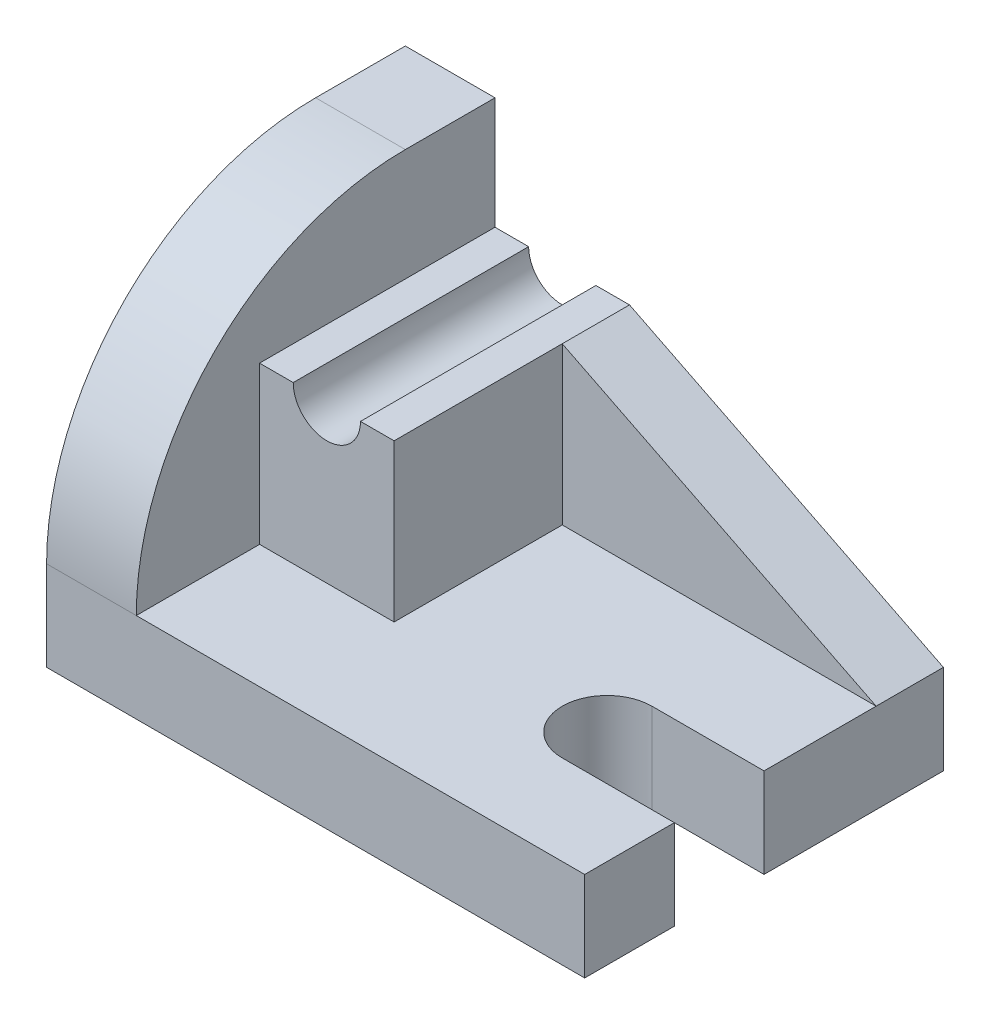
SolidWorks part; units mm, degrees
ref_plane "Front Plane" through (0, 0, 0) normal (0, 0, 1) x (1, 0, 0)
ref_plane "Top Plane" through (0, 0, 0) normal (0, 1, 0) x (1, 0, 0)
ref_plane "Right Plane" through (0, 0, 0) normal (1, 0, 0) x (0, 0, -1)
sketch "Sketch2" plane through (0, 0, 0) normal (0, 1, 0) x (1, 0, 0)
  line L1 (-48, -32) -> (48, -32)
  line L2 (-48, -32) -> (-48, 32)
  line L3 (-48, 32) -> (48, 32)
  line L4 (48, -32) -> (48, 32)
  line L5 (-48, -32) -> (48, 32) construction
  line L6 (-48, 32) -> (48, -32) construction
  point P0 (0, 0)
  dimension "D1" = 96
  dimension "D2" = 64
extrude "Boss-Extrude1" add sketch "Sketch2" along normal blind 16
sketch "Sketch5" plane through (0, 16, 0) normal (0, 1, 0) x (1, 0, 0)
  line L0 (48, -8) -> (28, -8) construction
  line L1 (48, -32) -> (48, 32) construction
  line L2 (48, -16) -> (28, -16)
  line L3 (48, 0) -> (28, 0)
  line L4 (-48, -32) -> (48, -32) construction
  arc A0 (48, -16) -> (48, 0) centre (48, -8) ccw
  arc A1 (28, 0) -> (28, -16) centre (28, -8) ccw
  point P4 (38, -8)
  dimension "D1" = 16
  dimension "D2" = 20
  dimension "D3" = 16
extrude "Cut-Extrude1" cut sketch "Sketch5" against normal blind 16
sketch "Sketch10" plane through (-48, 0, 0) normal (-1, 0, 0) x (0, 0, 1)
  line L1 (32, 0) -> (-32, 0)
  line L2 (32, 0) -> (32, 16)
  line L3 (-16, 64) -> (-32, 64)
  line L4 (-32, 0) -> (-32, 64)
  arc A0 (32, 16) -> (-16, 64) centre (-16, 16) ccw
  point P7 (32, 64)
  dimension "D2" = 48
  dimension "D1" = 64
extrude "Boss-Extrude2" add sketch "Sketch10" against normal blind 16
sketch "Sketch11" plane through (0, 16, 0) normal (0, 1, 0) x (1, 0, 0)
  line L0 (-32, -32) -> (48, -32) construction
  line L1 (-32, 32) -> (-8, 32)
  line L2 (-32, 32) -> (-32, -10)
  line L3 (-32, -10) -> (-8, -10)
  line L4 (-8, 32) -> (-8, -10)
  dimension "D1" = 22
  dimension "D2" = 24
extrude "Boss-Extrude3" add sketch "Sketch11" along normal blind 28
sketch "Sketch15" plane through (0, 0, -32) normal (0, 0, -1) x (-1, 0, 0)
  line L0 (-48, 16) -> (8, 44)
  line L1 (8, 44) -> (8, 16)
  line L2 (8, 16) -> (-48, 16)
extrude "Boss-Extrude4" add sketch "Sketch15" against normal blind 12
sketch "Sketch16" plane through (0, 0, -32) normal (0, 0, -1) x (-1, 0, 0)
  line L0 (8, 44) -> (32, 44) construction
  circle A0 centre (20, 44) radius 6
extrude "Cut-Extrude2" cut sketch "Sketch16" against normal up to vertex
